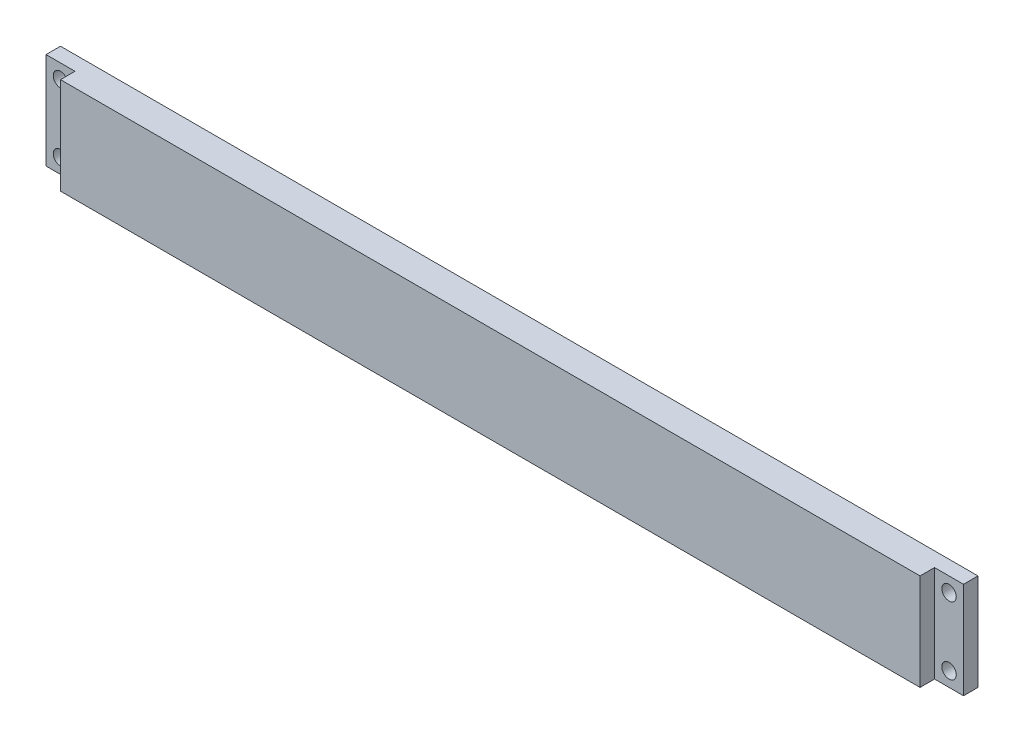
SolidWorks part; units mm, degrees
ref_plane "Plan de face" through (0, 0, 0) normal (0, 0, 1) x (1, 0, 0)
ref_plane "Plan de dessus" through (0, 0, 0) normal (0, 1, 0) x (1, 0, 0)
ref_plane "Plan de droite" through (0, 0, 0) normal (1, 0, 0) x (0, 0, -1)
sketch "Esquisse1" plane through (0, 0, 0) normal (0, 0, 1) x (1, 0, 0)
  line L1 (-95, 10) -> (95, 10)
  line L2 (-95, 10) -> (-95, -10)
  line L3 (-95, -10) -> (95, -10)
  line L4 (95, 10) -> (95, -10)
  dimension "D1" = 20
  dimension "D2" = 190
  dimension "D3" = 95
  dimension "D4" = 10
extrude "Boss.-Extru.1" add sketch "Esquisse1" along normal blind 6
sketch "Esquisse2" plane through (0, 0, 6) normal (0, 0, 1) x (1, 0, 0)
  line L0 (-95, -10) -> (95, -10) construction
  line L1 (-95, 10) -> (-89, 10)
  line L2 (-95, 10) -> (-95, -10)
  line L3 (-95, -10) -> (-89, -10)
  line L4 (-89, 10) -> (-89, -10)
  line L5 (0, 44.6188) -> (0, -56.7962) construction
  line L6 (89, 10) -> (89, -10)
  line L7 (95, -10) -> (89, -10)
  line L8 (95, 10) -> (95, -10)
  line L9 (95, 10) -> (89, 10)
  dimension "D1" = 6
extrude "Enlèv. mat.-Extru.1" cut sketch "Esquisse2" against normal blind 3
sketch "Esquisse3" plane through (0, 0, 0) normal (0, 0, -1) x (-1, 0, 0)
  line L0 (0, 35.3729) -> (0, -60.544) construction
  line L1 (-92, 28.3174) -> (-92, -47.3864) construction
  line L2 (-95, -10) -> (-95, 10) construction
  line L3 (95, -10) -> (-95, -10) construction
  line L4 (-95, 10) -> (95, 10) construction
  circle A0 centre (-92, -7) radius 1.5
  circle A1 centre (-92, 7) radius 1.5
  circle A2 centre (92, 7) radius 1.5
  circle A3 centre (92, -7) radius 1.5
  dimension "D2" = 3
  dimension "D3" = 3
  dimension "D4" = 3
  dimension "D5" = 3
  dimension "D1" = 3
extrude "Enlèv. mat.-Extru.2" cut sketch "Esquisse3" against normal blind 6
equation "\"D3@Esquisse1\"=\"D2@Esquisse1\"/2"
equation "\"D4@Esquisse1\"=\"D1@Esquisse1\"/2"
